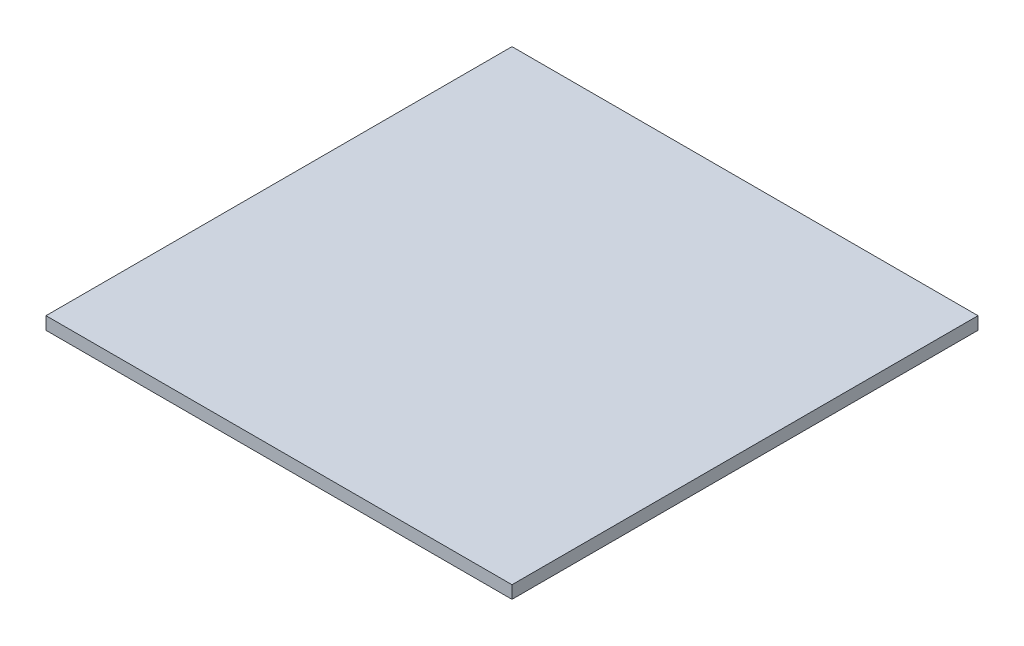
SolidWorks part; units mm, degrees
material "有机玻璃 (TM) GS 丙烯酸铸钣"
ref_plane "前视基准面" through (0, 0, 0) normal (0, 0, 1) x (1, 0, 0)
ref_plane "上视基准面" through (0, 0, 0) normal (0, 1, 0) x (1, 0, 0)
ref_plane "右视基准面" through (0, 0, 0) normal (1, 0, 0) x (0, 0, -1)
other "Configuration Table"
sketch "草图1" plane through (0, 0, 0) normal (0, 1, 0) x (1, 0, 0)
  line L1 (-275, 275) -> (275, 275)
  line L2 (-275, 275) -> (-275, -275)
  line L3 (-275, -275) -> (275, -275)
  line L4 (275, 275) -> (275, -275)
  line L5 (-275, 275) -> (275, -275) construction
  line L6 (-275, -275) -> (275, 275) construction
  point P0 (0, 0)
  dimension "D1" = 550
  dimension "D2" = 550
extrude "凸台-拉伸1" add sketch "草图1" along normal blind 15
